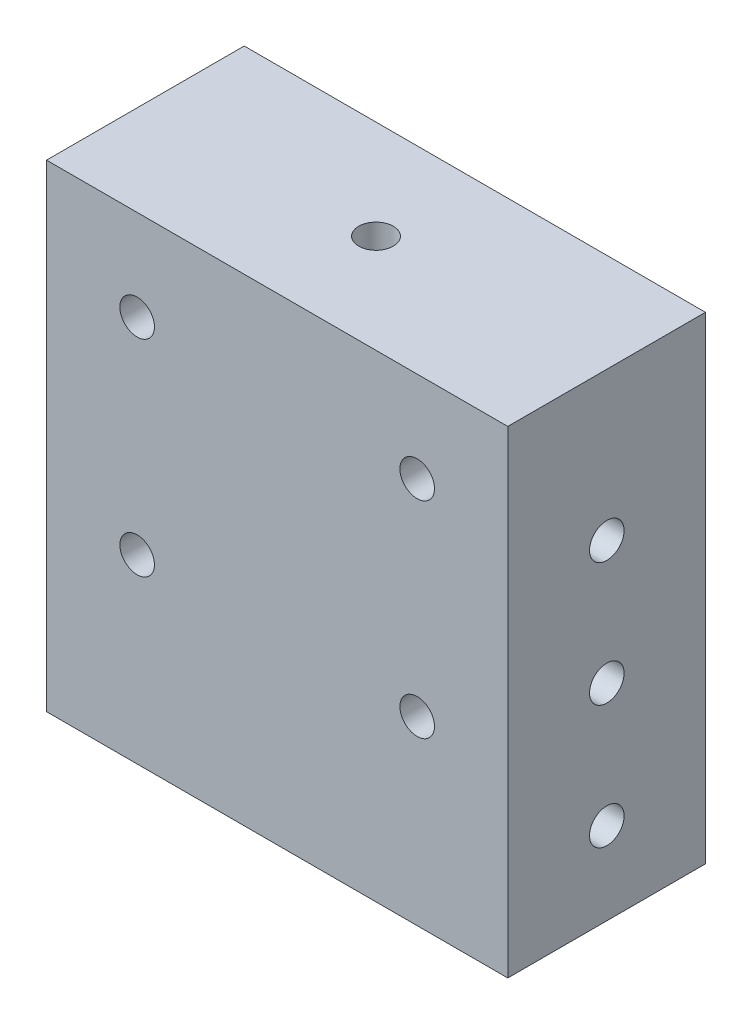
SolidWorks part; units mm, degrees
material "3.0517 (EN-AW 3003)"
ref_plane "Front Plane" through (0, 0, 0) normal (0, 0, 1) x (1, 0, 0)
ref_plane "Top Plane" through (0, 0, 0) normal (0, 1, 0) x (1, 0, 0)
ref_plane "Right Plane" through (0, 0, 0) normal (1, 0, 0) x (0, 0, -1)
sketch "Sketch1" plane through (0, 0, 0) normal (0, 0, 1) x (1, 0, 0)
  line L1 (20, -25) -> (-20, -25)
  line L2 (20, -25) -> (20, 25)
  line L3 (20, 25) -> (-20, 25)
  line L4 (-20, -25) -> (-20, 25)
  line L5 (20, -25) -> (-20, 25) construction
  line L6 (20, 25) -> (-20, -25) construction
  point P0 (0, 0)
  dimension "D1" = 40
  dimension "D2" = 50
extrude "Boss-Extrude1" add sketch "Sketch1" along normal mid plane 8
sketch "Sketch2" plane through (20, 0, 0) normal (1, 0, 0) x (0, 0, -1)
  line L0 (-4, -25) -> (-4, 33)
  line L1 (-4, 33) -> (20, 33)
  line L2 (20, 33) -> (20, -25)
  line L3 (20, -25) -> (-4, -25)
  line L4 (4, -25) -> (4, 25) construction
  line L5 (-4, 25) -> (4, 25) construction
  dimension "D1" = 16
  dimension "D2" = 8
extrude "Boss-Extrude2" add sketch "Sketch2" along normal blind 8
sketch "Sketch4" plane through (-20, 0, 0) normal (-1, 0, 0) x (0, 0, 1)
  line L0 (4, -25) -> (-20, -25)
  line L1 (-20, -25) -> (-20, 33)
  line L2 (4, -25) -> (4, 33)
  line L3 (4, 33) -> (-20, 33)
  line L4 (-4, 25) -> (-4, -25) construction
  line L5 (4, 25) -> (-4, 25) construction
  dimension "D1" = 16
  dimension "D2" = 8
extrude "Boss-Extrude3" add sketch "Sketch4" along normal blind 8
sketch "Sketch5" plane through (20, 0, 0) normal (-1, 0, 0) x (0, 0, 1)
  line L0 (-20, -25) -> (-20, 33)
  line L1 (-20, 33) -> (4, 33)
  line L2 (4, 33) -> (4, 25)
  line L3 (4, 25) -> (-12.05, 25)
  line L4 (-12.05, 25) -> (-12.05, -25)
  line L5 (-4, -25) -> (-20, -25) construction
  line L6 (-12.05, -25) -> (-20, -25)
  dimension "D1" = 7.95
extrude "Boss-Extrude5" add sketch "Sketch5" along normal up to surface (40 mm away) from surface at 0 contours L6 L0 L1 L2 L3 L4 up to face at (-20, 11, -6.6667) starting at face at (20, 11, -6.6667)
sketch "Sketch6" plane through (0, 0, -20) normal (0, 0, -1) x (-1, 0, 0)
  line L0 (-16, -25) -> (-16, 25)
  line L1 (-28, -25) -> (28, -25) construction
  line L2 (-16, 25) -> (16, 25)
  line L3 (16, 25) -> (16, -25)
  line L4 (-28, -25) -> (-28, 33) construction
  line L5 (28, 33) -> (28, -25) construction
  line L6 (16, -25) -> (-16, -25)
  dimension "D1" = 12
  dimension "D2" = 12
  dimension "D3" = 50
extrude "Cut-Extrude1" cut sketch "Sketch6" against normal blind 8
sketch "Sketch7" plane through (0, 33, 0) normal (0, 1, 0) x (1, 0, 0)
  line L0 (28, 8) -> (-28, 8) construction
  line L1 (28, 20) -> (28, -4) construction
  line L2 (-28, -4) -> (-28, 20) construction
  line L3 (0, 20) -> (0, -4) construction
  line L4 (28, 20) -> (-28, 20) construction
  line L5 (28, -4) -> (-28, -4) construction
  circle A0 centre (0, 8) radius 2.1
  dimension "D1" = 4.2
sketch "Sketch9" plane through (20, 0, 0) normal (-1, 0, 0) x (0, 0, 1)
  line L0 (-8.025, -25) -> (-8.025, 25) construction
  line L1 (-4, -25) -> (-12.05, -25) construction
  line L2 (-12.05, 25) -> (-4, 25) construction
  line L4 (-4, -25) -> (-4, 25) construction
  line L6 (-4, 0) -> (-12.05, 0) construction
  circle A0 centre (-8.025, 0) radius 2.1
  circle A1 centre (-8.025, 15) radius 2.1
  circle A2 centre (-8.025, -15) radius 2.1
  dimension "D3" = 4.2
  dimension "D4" = 15
  dimension "D1" = 25
  dimension "D2" = 8.05
  dimension "D5" = 15
sketch "Sketch24" plane through (0, 0, 4) normal (0, 0, 1) x (1, 0, 0)
  line L0 (-17, 33) -> (-17, -25) construction
  line L1 (28, 33) -> (-28, 33) construction
  line L2 (0, 33) -> (0, -3) construction
  line L4 (-28, 22) -> (28, 22) construction
  line L5 (-28, -25) -> (-28, 33) construction
  line L6 (-28, -3) -> (28, -3) construction
  line L7 (-28, -25) -> (28, -25) construction
  line L8 (17, 33) -> (17, -25) construction
  circle A0 centre (-17, 22) radius 2.1
  circle A1 centre (-17, -3) radius 2.1
  circle A2 centre (17, -3) radius 2.1
  circle A3 centre (17, 22) radius 2.1
  point P24 (0, -3)
  point P25 (0, 22)
  dimension "D4" = 4.2
  dimension "D1" = 22
  dimension "D2" = 11
  dimension "D3" = 11
hole_wizard "M5 Tapped Hole3" positions "Sketch34" profile "Sketch35" tap size "M5" standard "DIN"
sketch "Sketch34" plane through (0, 0, -4) normal (0, 0, -1) x (-1, 0, 0)
  line L0 (-20, 25) -> (20, 25) construction
  line L1 (20, 25) -> (20, -25) construction
  line L2 (-20, -25) -> (-20, 25) construction
  point P0 (-17, 22)
  point P2 (17, 22)
  point P4 (17, -3)
  point P6 (-17, -3)
  dimension "D1" = 3
  dimension "D2" = 3
  dimension "D3" = 3
  dimension "D4" = 25
  dimension "D5" = 34
  dimension "D6" = 3
  dimension "D7" = 3
  dimension "D8" = 34
  dimension "D9" = 25
sketch "Sketch35" plane through (17, 22, -4) normal (1, 0, 0) x (0, 1, 0)
  line L0 (0, 0) -> (0, 8)
  line L1 (0, 8) -> (2.1, 8)
  line L2 (2.1, 8) -> (2.1, 0)
  line L5 (2.1, 0) -> (0, 0)
  line L11 (0, -6.35) -> (0, 107.95) construction
  dimension "Thru Tap Drill Dia." = 4.2
  dimension "Thru Tap Drill Depth" = 8
cosmetic thread "Hole Thread1" parameters "D2"=5
cosmetic thread "Hole Thread2" parameters "D2"=5
cosmetic thread "Hole Thread3" parameters "D2"=5
cosmetic thread "Hole Thread4" parameters "D2"=5
hole_wizard "M5 Tapped Hole4" positions "Sketch36" profile "Sketch37" tap size "M5" standard "DIN" end condition through all
sketch "Sketch36" plane through (0, 33, 0) normal (0, 1, 0) x (1, 0, 0)
  point P0 (0, 8)
sketch "Sketch37" plane through (0, 33, -8) normal (1, 0, 0) x (0, 0, 1)
  line L0 (0, 0) -> (0, 58)
  line L1 (0, 58) -> (2.1, 58)
  line L2 (2.1, 58) -> (2.1, 0)
  line L5 (2.1, 0) -> (0, 0)
  line L11 (0, -6.35) -> (0, 107.95) construction
  dimension "Thru Tap Drill Dia." = 4.2
  dimension "Thru Tap Drill Depth" = 58
cosmetic thread "Hole Thread5" parameters "D2"=5
hole_wizard "M5 Tapped Hole5" positions "Sketch38" profile "Sketch39" tap size "M5" standard "DIN"
sketch "Sketch38" plane through (28, 0, 0) normal (1, 0, 0) x (0, 0, -1)
  point P0 (8.025, 15)
  point P3 (8.025, 0)
  point P6 (8.025, -15)
sketch "Sketch39" plane through (28, 15, -8.025) normal (0, 1, 0) x (0, 0, -1)
  line L0 (0, 0) -> (0, 8)
  line L1 (0, 8) -> (2.1, 8)
  line L2 (2.1, 8) -> (2.1, 0)
  line L5 (2.1, 0) -> (0, 0)
  line L11 (0, -6.35) -> (0, 107.95) construction
  dimension "Thru Tap Drill Dia." = 4.2
  dimension "Thru Tap Drill Depth" = 8
cosmetic thread "Hole Thread6" parameters "D2"=5
cosmetic thread "Hole Thread7" parameters "D2"=5
cosmetic thread "Hole Thread8" parameters "D2"=5
